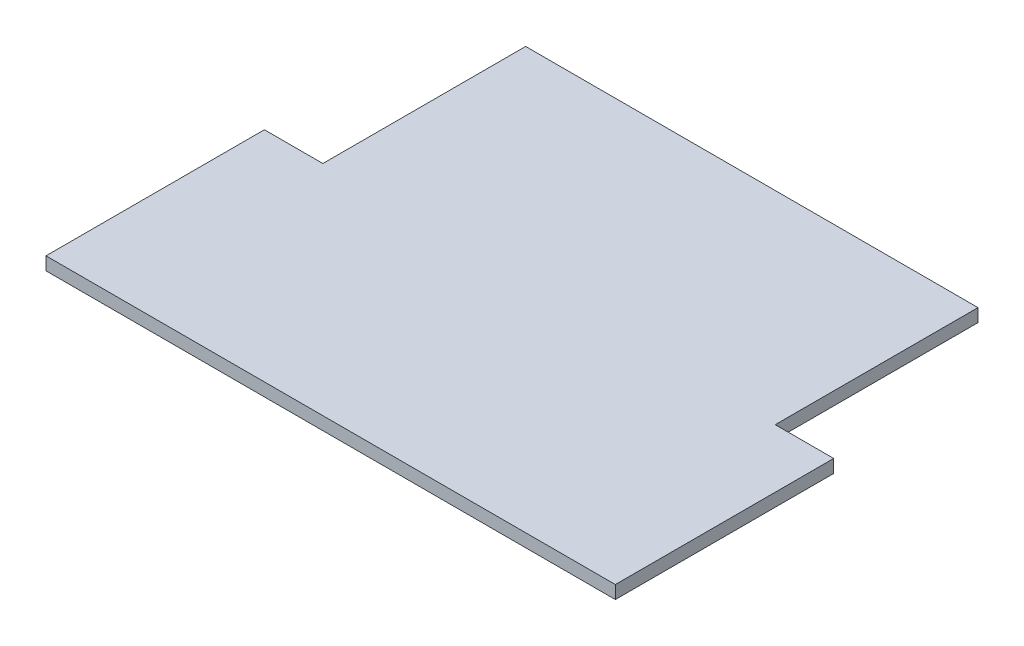
SolidWorks part; units mm, degrees
ref_plane "Front Plane" through (0, 0, 0) normal (0, 0, 1) x (1, 0, 0)
ref_plane "Top Plane" through (0, 0, 0) normal (0, 1, 0) x (1, 0, 0)
ref_plane "Right Plane" through (0, 0, 0) normal (1, 0, 0) x (0, 0, -1)
sketch "Sketch1" plane through (0, 0, 0) normal (0, 1, 0) x (1, 0, 0)
  line L0 (-36.5, -27) -> (-36.5, 1)
  line L1 (36.5, 27) -> (-36.5, 27) construction
  line L2 (36.5, 27) -> (36.5, -27) construction
  line L3 (36.5, -27) -> (-36.5, -27)
  line L4 (-36.5, 27) -> (-36.5, -27) construction
  line L5 (36.5, 27) -> (-36.5, -27) construction
  line L6 (36.5, -27) -> (-36.5, 27) construction
  line L7 (-36.5, 1) -> (-29, 1)
  line L8 (-29, 1) -> (-29, 27)
  line L9 (-29, 27) -> (29, 27)
  line L10 (0, 27) -> (0, 0) construction
  line L11 (36.5, -27) -> (36.5, 1)
  line L12 (36.5, 1) -> (29, 1)
  line L13 (29, 1) -> (29, 27)
  point P0 (0, 0)
  dimension "D1" = 73
  dimension "D2" = 54
  dimension "D3" = 7.5
  dimension "D4" = 28
extrude "Boss-Extrude1" add sketch "Sketch1" along normal blind 1.67
